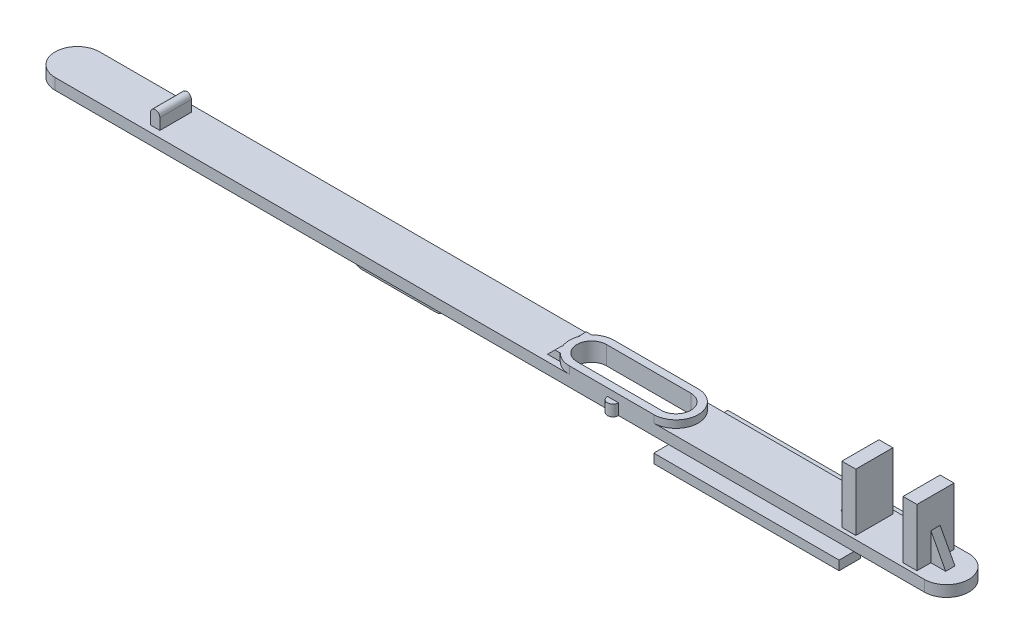
SolidWorks part; units mm, degrees
ref_plane "Front Plane" through (0, 0, 0) normal (0, 0, 1) x (1, 0, 0)
ref_plane "Top Plane" through (0, 0, 0) normal (0, 1, 0) x (1, 0, 0)
ref_plane "Right Plane" through (0, 0, 0) normal (1, 0, 0) x (0, 0, -1)
ref_plane "Plane1" through (0, 0, 0) normal (0, -1, 0) x (1, 0, 0)
sketch "Sketch1" plane through (0, 0, 0) normal (0, -1, 0) x (1, 0, 0)
  line L0 (46.9, 2.4) -> (-46.9, 2.4)
  line L1 (-46.9, -2.4) -> (46.9, -2.4)
  arc A0 (46.9, -2.4) -> (46.9, 2.4) centre (46.9, 0) ccw
  arc A1 (-46.9, 2.4) -> (-46.9, -2.4) centre (-46.9, 0) ccw
extrude "Boss-Extrude1" add sketch "Sketch1" against normal blind 1.2
sketch "Sketch2" plane through (0, 1.2, 0) normal (0, 1, 0) x (-1, 0, 0)
  line L0 (-6.33, 2.4) -> (-6.33, 0.918)
  line L1 (-6.33, 0.918) -> (-6.3825, 0.918)
  line L2 (-6.3825, -0.918) -> (-6.33, -0.918)
  line L3 (-6.33, -0.918) -> (-6.33, -2.4)
  line L4 (-6.33, -2.4) -> (-17.7, -2.4)
  line L5 (-17.7, 2.4) -> (-6.33, 2.4)
  arc A0 (-6.3825, 0.918) -> (-6.3825, -0.918) centre (-8.6, 0) cw
  arc A1 (-17.7, -2.4) -> (-17.7, 2.4) centre (-17.7, 0) cw
extrude "Boss-Extrude2" add sketch "Sketch2" along normal blind 0.8
sketch "Sketch3" plane through (0, 0, 0) normal (0, -1, 0) x (1, 0, 0)
  line L0 (39.3, 1.7) -> (19.3, 1.7)
  line L1 (19.3, 1.7) -> (19.3, 4)
  line L2 (19.3, 4) -> (39.3, 4)
  line L3 (39.3, 4) -> (39.3, 1.7)
extrude "Boss-Extrude3" add sketch "Sketch3" along normal blind 1
sketch "Sketch4" plane through (0, 0, 0) normal (0, -1, 0) x (1, 0, 0)
  line L0 (19.3, -1.7) -> (39.3, -1.7)
  line L1 (39.3, -1.7) -> (39.3, -4)
  line L2 (39.3, -4) -> (19.3, -4)
  line L3 (19.3, -4) -> (19.3, -1.7)
extrude "Boss-Extrude4" add sketch "Sketch4" along normal blind 1
sketch "Sketch5" plane through (0, 2, 0) normal (0, 1, 0) x (-1, 0, 0)
  line L0 (-8.6, -2.4) -> (-6.33, -2.4)
  line L1 (-6.33, -2.4) -> (-6.33, -1.697)
  line L2 (-6.33, -1.697) -> (-6.9029, -1.697)
  arc A0 (-6.9029, -1.697) -> (-8.6, -2.4) centre (-8.6, 0) cw
extrude "Cut-Extrude1" cut sketch "Sketch5" against normal blind 0.8
sketch "Sketch6" plane through (0, 2, 0) normal (0, 1, 0) x (-1, 0, 0)
  line L0 (-6.9029, 1.697) -> (-6.33, 1.697)
  line L1 (-6.33, 1.697) -> (-6.33, 2.4)
  line L2 (-6.33, 2.4) -> (-8.6, 2.4)
  arc A0 (-8.6, 2.4) -> (-6.9029, 1.697) centre (-8.6, 0) cw
extrude "Cut-Extrude2" cut sketch "Sketch6" against normal blind 0.8
sketch "Sketch7" plane through (0, 0, 0) normal (0, -1, 0) x (1, 0, 0)
  line L0 (17.7, 1.6) -> (8.6, 1.6)
  line L1 (8.6, -1.6) -> (17.7, -1.6)
  arc A0 (8.6, 1.6) -> (8.6, -1.6) centre (8.6, 0) ccw
  arc A1 (17.7, -1.6) -> (17.7, 1.6) centre (17.7, 0) ccw
extrude "Cut-Extrude3" cut sketch "Sketch7" against normal through all
sketch "Sketch8" plane through (0, 0, 0) normal (0, -1, 0) x (1, 0, 0)
  line L0 (12.7, 2.4) -> (13.9, 2.4)
  arc A0 (13.9, 2.4) -> (12.7, 2.4) centre (13.3, 2.4) ccw
extrude "Boss-Extrude5" add sketch "Sketch8" against normal blind 1.2
sketch "Sketch9" plane through (0, 0, 0) normal (0, -1, 0) x (1, 0, 0)
  line L0 (13.9, -2.4) -> (12.7, -2.4)
  arc A0 (12.7, -2.4) -> (13.9, -2.4) centre (13.3, -2.4) ccw
extrude "Boss-Extrude6" add sketch "Sketch9" against normal blind 1.2
sketch "Sketch10" plane through (0, 1.2, 0) normal (0, 1, 0) x (-1, 0, 0)
  line L0 (-37.6, -2) -> (-39.1, -2)
  line L1 (-39.1, -2) -> (-39.1, 2)
  line L2 (-39.1, 2) -> (-37.6, 2)
  line L3 (-37.6, 2) -> (-37.6, -2)
extrude "Boss-Extrude7" add sketch "Sketch10" along normal blind 6.2
sketch "Sketch11" plane through (0, 1.2, 0) normal (0, 1, 0) x (-1, 0, 0)
  line L0 (-44.2, -2) -> (-45.7, -2)
  line L1 (-45.7, -2) -> (-45.7, 2)
  line L2 (-45.7, 2) -> (-44.2, 2)
  line L3 (-44.2, 2) -> (-44.2, -2)
extrude "Boss-Extrude8" add sketch "Sketch11" along normal blind 6.2
ref_plane "Plane2" through (0, 0, -1.7) normal (0, 0, -1) x (-1, 0, 0)
sketch "Sketch12" plane through (0, 0, -1.7) normal (0, 0, -1) x (-1, 0, 0)
  line L0 (36.3, 1.2) -> (37.3, 1.2)
  line L1 (37.3, 1.2) -> (37.3, 2.4)
  line L2 (36.3, 2.4) -> (36.3, 1.2)
  arc A0 (37.3, 2.4) -> (36.3, 2.4) centre (36.8, 2.4) ccw
extrude "Boss-Extrude9" add sketch "Sketch12" against normal blind 3.4
ref_plane "Plane3" through (0, 0, -1.6) normal (0, 0, -1) x (-1, 0, 0)
sketch "Sketch13" plane through (0, 0, -1.6) normal (0, 0, -1) x (-1, 0, 0)
  line L0 (46.5, 0) -> (36.5, 0)
  line L1 (37.5, -1) -> (45.5, -1)
  arc A0 (45.5, -1) -> (46.5, 0) centre (45.5, 0) ccw
  arc A1 (36.5, 0) -> (37.5, -1) centre (37.5, 0) ccw
extrude "Boss-Extrude10" add sketch "Sketch13" against normal blind 1
ref_plane "Plane4" through (0, 0, 0.6) normal (0, 0, -1) x (-1, 0, 0)
sketch "Sketch14" plane through (0, 0, 0.6) normal (0, 0, -1) x (-1, 0, 0)
  line L0 (15.6, 0) -> (5.6, 0)
  line L1 (6.6, -1) -> (14.6, -1)
  arc A0 (14.6, -1) -> (15.6, 0) centre (14.6, 0) ccw
  arc A1 (5.6, 0) -> (6.6, -1) centre (6.6, 0) ccw
extrude "Boss-Extrude11" add sketch "Sketch14" against normal blind 1
draft "Draft1" type of draft neutral plane draft angle 45 faces to draft 2 face at (6.33, 1.6, -1.3075) face at (6.33, 1.6, 1.3075) neutral plane through (8.6, 2, 0) neutral plane normal (0, 1, 0) parameters "D1"=45
ref_plane "Plane5" through (0, 0, 0) normal (0, 0, -1) x (-1, 0, 0)
sketch "Sketch15" plane through (0, 0, 0) normal (0, 0, -1) x (-1, 0, 0)
  line L0 (25.15, -0.4) -> (26.05, -0.4)
  line L1 (26.05, -0.4) -> (26.05, 0)
  line L2 (26.05, 0) -> (25.15, 0)
  line L3 (25.15, 0) -> (25.15, -0.4)
  line L4 (26.05, -0.4) -> (26.05, 0) construction
revolve "Revolve1" add sketch "Sketch15" angle 360 about L4
sketch "Sketch16" plane through (0, 0, 0) normal (0, 0, -1) x (-1, 0, 0)
  line L0 (33.15, -0.4) -> (34.05, -0.4)
  line L1 (34.05, -0.4) -> (34.05, 0)
  line L2 (34.05, 0) -> (33.15, 0)
  line L3 (33.15, 0) -> (33.15, -0.4)
  line L4 (34.05, -0.4) -> (34.05, 0) construction
revolve "Revolve2" add sketch "Sketch16" angle 360 about L4
sketch "Sketch17" plane through (0, 0, 0) normal (0, 0, -1) x (-1, 0, 0)
  line L0 (17.15, -0.4) -> (18.05, -0.4)
  line L1 (18.05, -0.4) -> (18.05, 0)
  line L2 (18.05, 0) -> (17.15, 0)
  line L3 (17.15, 0) -> (17.15, -0.4)
  line L4 (18.05, -0.4) -> (18.05, 0) construction
revolve "Revolve3" add sketch "Sketch17" angle 360 about L4
sketch "Sketch18" plane through (0, 0, 0) normal (0, 0, -1) x (-1, 0, 0)
  line L0 (-45.7, 4.2) -> (-47.3, 1.2)
rib "Rib1" sketch "Sketch18" sketch "Sketch18" thickness 1 extrusion direction parallel to sketch draft on no parameters "D1"=1
sketch "Sketch19" plane through (0, 0, 0) normal (0, 0, 1) x (1, 0, 0)
  line L0 (37.6, 4.2) -> (36, 1.2)
rib "Rib2" sketch "Sketch19" sketch "Sketch19" thickness 1 extrusion direction parallel to sketch draft on no parameters "D1"=1
fillet "Fillet2" radius 0.1 1 edges at (13.3, 1.2, -3)
